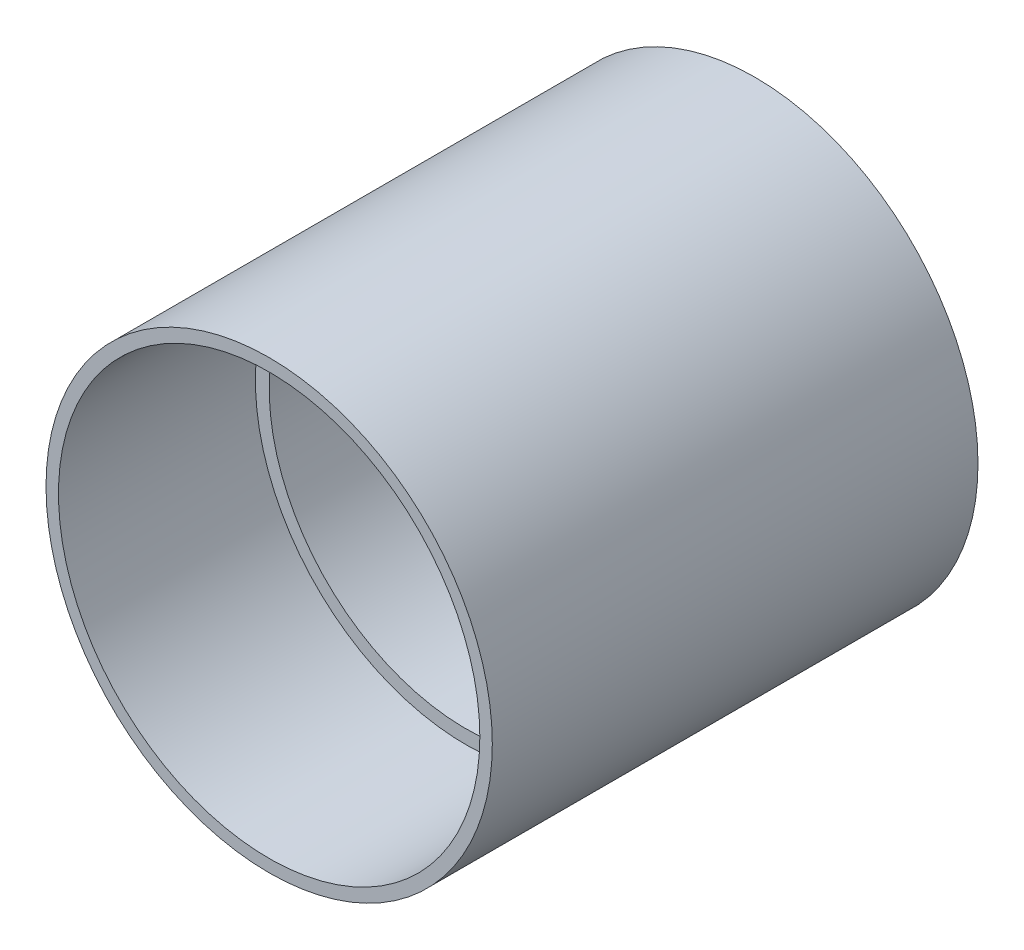
SolidWorks part; units mm, degrees
ref_plane "Front Plane" through (0, 0, 0) normal (0, 0, 1) x (1, 0, 0)
ref_plane "Top Plane" through (0, 0, 0) normal (0, 1, 0) x (1, 0, 0)
ref_plane "Right Plane" through (0, 0, 0) normal (1, 0, 0) x (0, 0, -1)
sketch "Sketch1" plane through (0, 0, 0) normal (0, 0, 1) x (1, 0, 0)
  circle A0 centre (0, 0) radius 34
extrude "Body" add sketch "Sketch1" along normal blind 74
ref_plane "Plane_z44" through (0, 0, 44) normal (0, 0, 1) x (1, 0, 0)
sketch "Sketch2" plane through (0, 0, 44) normal (0, 0, 1) x (1, 0, 0)
  circle A0 centre (0, 0) radius 32.1
extrude "Sleeve_bore" cut sketch "Sketch2" along normal blind 30
ref_plane "Plane_z4" through (0, 0, 4) normal (0, 0, 1) x (1, 0, 0)
sketch "Sketch3" plane through (0, 0, 4) normal (0, 0, 1) x (1, 0, 0)
  circle A0 centre (0, 0) radius 30
extrude "Chamber" cut sketch "Sketch3" along normal blind 40
fillet "Base_corner" radius 2 1 edges at (30, 0, 4)
